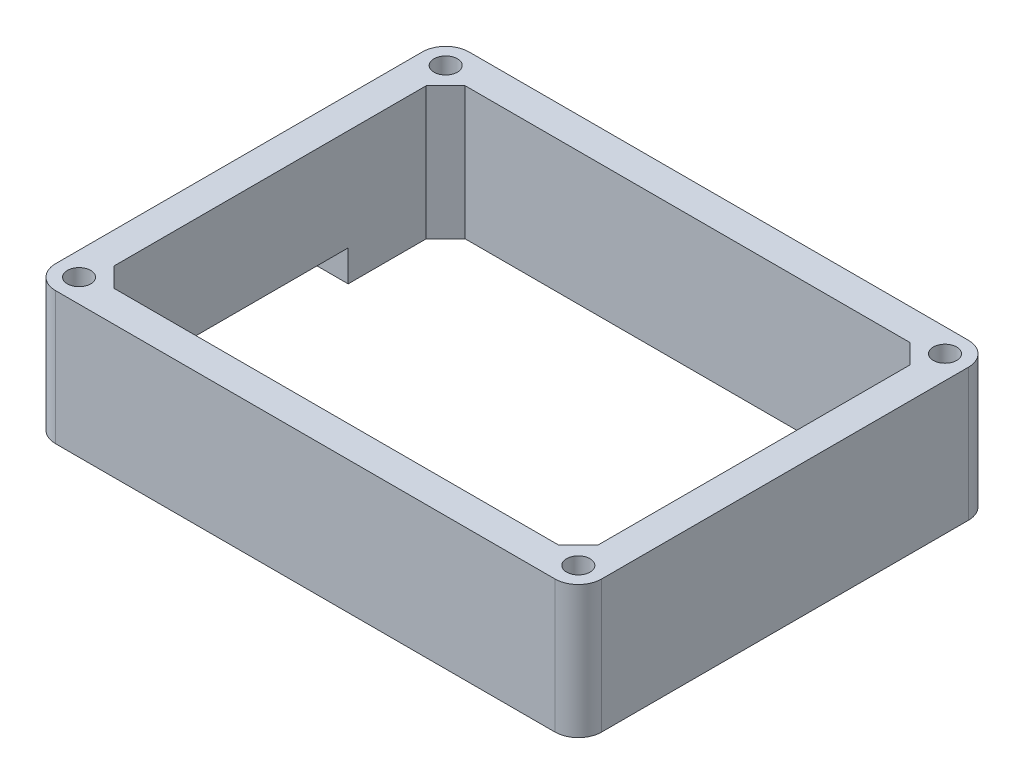
SolidWorks part; units mm, degrees
ref_plane "Front Plane" through (0, 0, 0) normal (0, 0, 1) x (1, 0, 0)
ref_plane "Top Plane" through (0, 0, 0) normal (0, 1, 0) x (1, 0, 0)
ref_plane "Right Plane" through (0, 0, 0) normal (1, 0, 0) x (0, 0, -1)
sketch "Sketch1" plane through (0, 0, 0) normal (0, 1, 0) x (1, 0, 0)
  line L0 (-113.315, 26.5) -> (53.9232, 26.5) construction
  line L1 (-3, 0) -> (-67, 0)
  line L2 (0, 3) -> (0, 50)
  line L3 (-3, 53) -> (-67, 53)
  line L4 (-70, 3) -> (-70, 50)
  line L9 (-35, 90.4705) -> (-35, -40.2911) construction
  line L10 (-66, 46.5) -> (-63.5, 49)
  line L11 (-97.6207, 44) -> (32.2457, 44) construction
  line L14 (-63.5, 49) -> (-6.5, 49)
  line L17 (-66, 46.5) -> (-66, 6.5)
  line L20 (-63.5, 4) -> (-6.5, 4)
  line L23 (-4, 46.5) -> (-4, 6.5)
  line L24 (-6.5, 49) -> (-4, 46.5)
  line L25 (-6.5, 4) -> (-4, 6.5)
  line L26 (-66, 6.5) -> (-63.5, 4)
  arc A0 (-67, 0) -> (-70, 3) centre (-67, 3) cw
  arc A1 (-3, 0) -> (0, 3) centre (-3, 3) ccw
  arc A2 (0, 50) -> (-3, 53) centre (-3, 50) ccw
  arc A3 (-67, 53) -> (-70, 50) centre (-67, 50) ccw
  circle A4 centre (-67, 50) radius 1.5
  circle A5 centre (-3, 50) radius 1.5
  circle A6 centre (-3, 3) radius 1.5
  circle A7 centre (-67, 3) radius 1.5
  point P7 (-70, 0)
  point P10 (0, 0)
  point P13 (0, 53)
  point P26 (-66, 49)
  point P27 (-4, 4)
  point P28 (-66, 4)
  point P29 (-4, 49)
  dimension "D3" = 3
  dimension "D4" = 3
  dimension "D5" = 35
  dimension "D1" = 53
  dimension "D2" = 70
  dimension "D6" = 26.5
  dimension "D7" = 45
  dimension "D8" = 62
  dimension "D9" = 4
  dimension "D10" = 4
extrude "Boss-Extrude1" add sketch "Sketch1" along normal blind 17
sketch "Sketch2" plane through (-70, 0, 0) normal (-1, 0, 0) x (0, 0, 1)
  line L0 (-50, 0) -> (-3, 0) construction
  line L1 (-36.5, 0) -> (-16.5, 0)
  line L2 (-36.5, 0) -> (-36.5, 4)
  line L3 (-36.5, 4) -> (-16.5, 4)
  line L4 (-16.5, 0) -> (-16.5, 4)
  line L5 (0, 17) -> (0, 0) construction
  dimension "D1" = 4
  dimension "D2" = 20
  dimension "D3" = 16.5
extrude "Cut-Extrude1" cut sketch "Sketch2" against normal up to surface (4 mm away) up to face at (-66, 8.5, -26.5)
